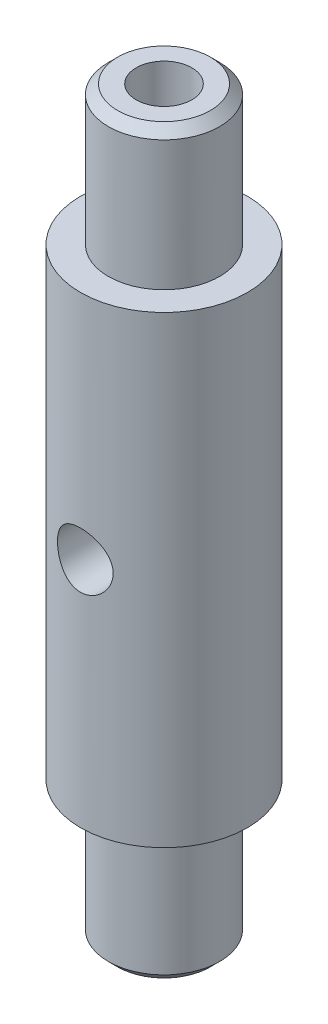
SolidWorks part; units mm, degrees
ref_plane "Front Plane" through (0, 0, 0) normal (0, 0, 1) x (1, 0, 0)
ref_plane "Top Plane" through (0, 0, 0) normal (0, 1, 0) x (1, 0, 0)
ref_plane "Right Plane" through (0, 0, 0) normal (1, 0, 0) x (0, 0, -1)
sketch "Sketch1" plane through (0, 0, 0) normal (0, 0, 1) x (1, 0, 0)
  line L0 (0, 37.5) -> (0, -45.0556) construction
  line L1 (0, 40) -> (6, 40)
  line L2 (6, 40) -> (6, 25)
  line L3 (6, 25) -> (9, 25)
  line L4 (9, 25) -> (9, -25)
  line L5 (-18.1111, 0) -> (19.2222, 0) construction
  line L6 (6, -25) -> (9, -25)
  line L7 (6, -40) -> (6, -25)
  line L8 (0, -40) -> (6, -40)
  line L9 (0, 40) -> (0, -40)
  point P11 (9, 0)
  dimension "D1" = 6
  dimension "D2" = 9
  dimension "D3" = 40
  dimension "D4" = 15
revolve "Revolve1" add sketch "Sketch1" angle 360 about L9
ref_plane "Plane1" through (0, 0, 10) normal (0, 0, 1) x (1, 0, 0)
sketch "Sketch2" plane through (0, 0, 10) normal (0, 0, 1) x (1, 0, 0)
  line L0 (9, 25) -> (-9, 25) construction
  circle A0 centre (0, 0) radius 3
  dimension "D1" = 6
  dimension "D2" = 25
extrude "Cut-Extrude1" cut sketch "Sketch2" against normal through all
chamfer "Chamfer1" distance 1 angle 45 1 edges at (0, -40, 6)
chamfer "Chamfer2" distance 1 angle 45 1 edges at (0, 40, 6)
sketch "Sketch5" plane through (0, 40, 0) normal (0, 1, 0) x (1, 0, 0)
  point P0 (0, 0)
hole_wizard "Ø6.0 (6) Diameter Hole1" positions "Sketch5" profile "Sketch6" hole size "Ø6.0" standard "DIN"
sketch "Sketch6" plane through (0, 40, 0) normal (1, 0, 0) x (0, 0, 1)
  line L0 (0, 0) -> (0, 46.8026)
  line L1 (0, 46.8026) -> (3, 45)
  line L2 (3, 45) -> (3, 0)
  line L5 (3, 0) -> (0, 0)
  line L10 (0, 46.8026) -> (-3, 45) construction
  line L11 (0, -6.35) -> (0, 107.95) construction
  dimension "Hole Dia." = 6
  dimension "Hole Depth" = 45
  dimension "Drill Angle" = 118
